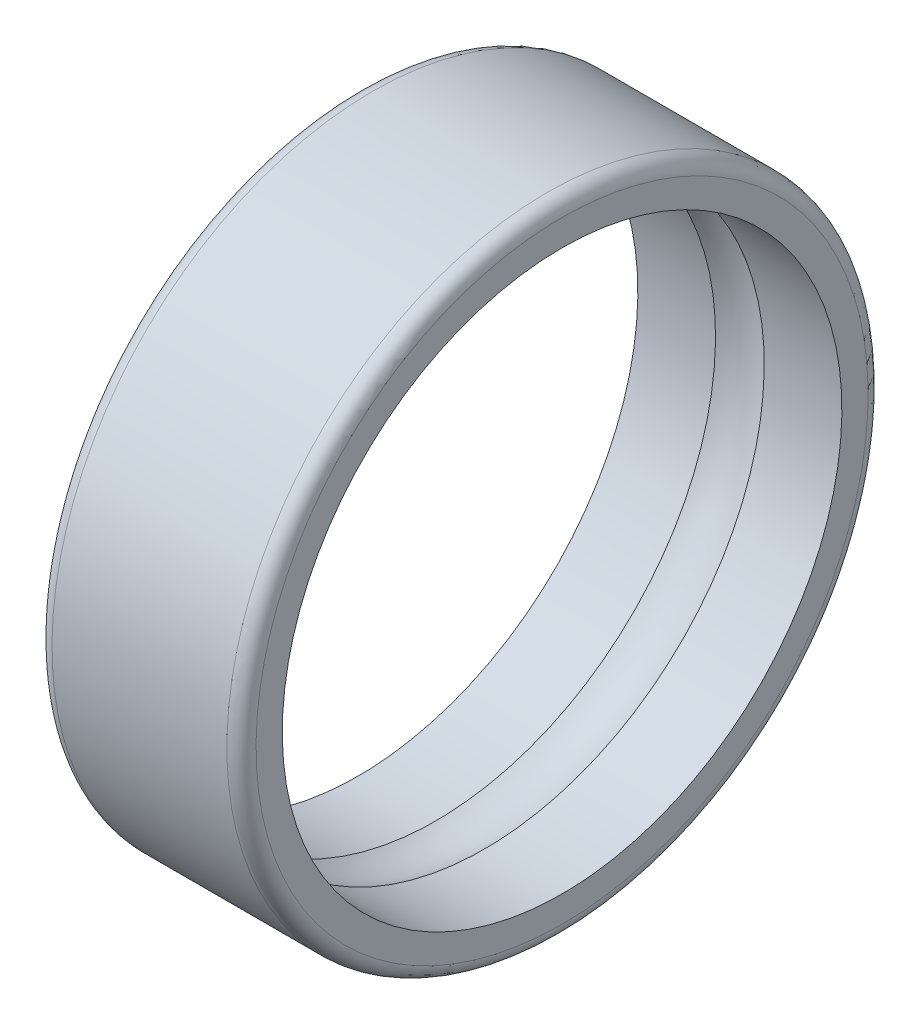
SolidWorks part; units mm, degrees
ref_plane "Front Plane" through (0, 0, 0) normal (0, 0, 1) x (1, 0, 0)
ref_plane "Top Plane" through (0, 0, 0) normal (0, 1, 0) x (1, 0, 0)
ref_plane "Right Plane" through (0, 0, 0) normal (1, 0, 0) x (0, 0, -1)
sketch "Sketch2" plane through (0, 0, 0) normal (0, 0, 1) x (1, 0, 0)
  line L0 (23.6602, 0) -> (-21.7547, 0) construction
  line L1 (3.5, 11) -> (-3.5, 11)
  line L2 (3.5, 11) -> (3.5, 9.6)
  line L3 (3.5, 9.6) -> (-3.5, 9.6)
  line L4 (-3.5, 9.6) -> (-3.5, 11)
  line L5 (3.5, 6.05) -> (3.5, 4)
  line L6 (3.5, 4) -> (-3.5, 4)
  line L7 (-3.5, 4) -> (-3.5, 6.05)
  line L8 (-3.5, 6.05) -> (3.5, 6.05)
  circle A0 centre (0, 7.8) radius 1.9845
  point P9 (0, 11)
  dimension "Ball Bearing Size" = 3.969
  dimension "Bearing Width" = 7
  dimension "Inner Casing Inner" = 4
  dimension "Inner Casing Outter" = 6.05
  dimension "Outter Casing Inner" = 9.6
  dimension "Outter Case Outter" = 11
  dimension "D1" = 1.75
revolve "Revolve1" add sketch "Sketch2" angle 360 about L0
fillet "Fillet1" radius 0.5 2 edges at (-3.5, 11, 0) (3.5, 11, 0)
equation "\"Motor Width\"= 42.3'eg: For stepper motor Nema 17 = 42.3mm"
equation "\"Motor Hole Config Width\"= 31'eg: For stepper motor Nema 17 = 31"
equation "\"Mounting Hole Diameter\"= 3'eg: For Nema 17 3mm"
equation "\"Motor Depth\"= 50'eg: For Nema 17 50mm"
equation "\"Exposed Shaft Length\"= 22'eg: For Nema 17 22mm"
equation "\"Shaft Seround Depthr\"= 2'eg: For Nema 17 2mm"
equation "\"Shaft Diameter\"= 5'eg: For Nema 17 5mm"
equation "\"Top/Bottom Casing Depth\"= 10'Guess"
equation "\"Mid Casing Depth\"= \"Motor Depth\" - 2 * ( \"Top/Bottom Casing Depth\" )"
equation "\"Bearing Outter Diameter\"= 22' From Spec 608z = 22mm"
equation "\"Shaft Clearance Hole\"= \"Shaft Diameter\"+1.5'Guess"
equation "\"Bearing Ball Size\"= 3.969'From Spec"
equation "\"Bearing Inner Case Inner Diameter\"= 8'From Spec"
equation "\"Bearing Inner Case Outter Diameter\"= 12.1'From Spec"
equation "\"Bearing Outter Case Inner Diameter\"= 19.2'From Spec"
equation "\"Bearing Width\"= 7'From Spec"
equation "\"Bearing Width@Sketch2\"=\"Bearing Width\""
equation "\"Inner Casing Inner@Sketch2\"=\"Bearing Inner Case Inner Diameter\"/2"
equation "\"Inner Casing Outter@Sketch2\"=\"Bearing Inner Case Outter Diameter\"/2"
equation "\"Outter Casing Inner@Sketch2\"=\"Bearing Outter Case Inner Diameter\"/2"
equation "\"Outter Case Outter@Sketch2\"=\"Bearing Outter Diameter\"/2"
equation "\"Ball Bearing Size@Sketch2\"=\"Bearing Ball Size\""
